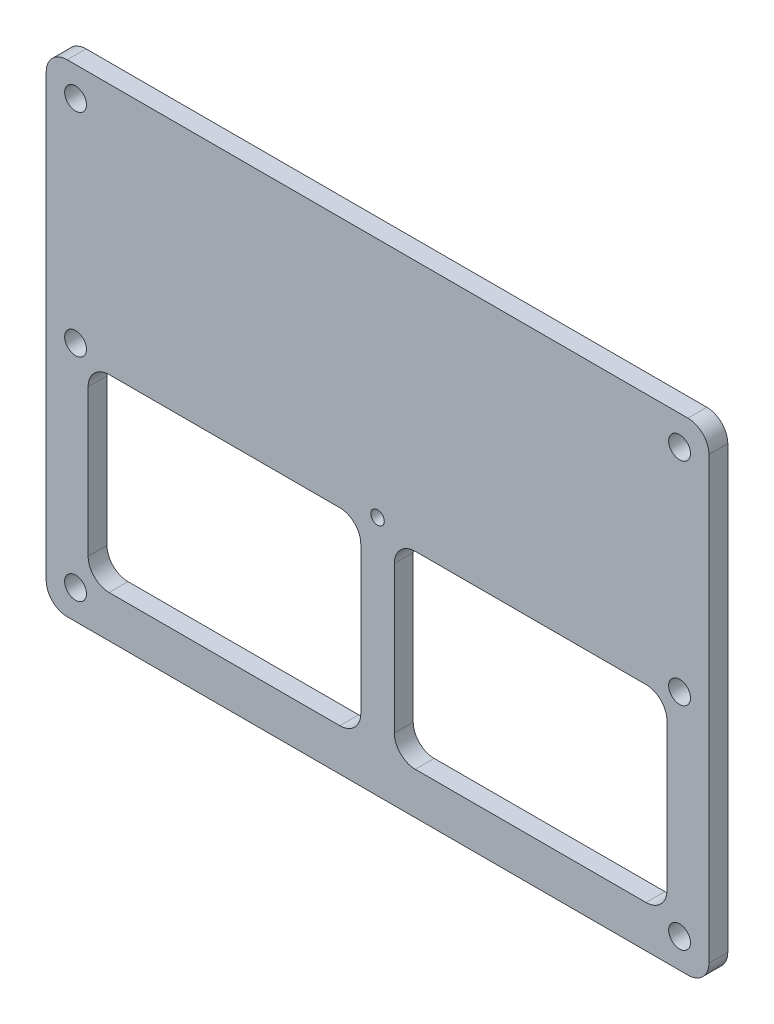
SolidWorks part; units mm, degrees
material "ABS PC"
ref_plane "前视基准面" through (0, 0, 0) normal (0, 0, 1) x (1, 0, 0)
ref_plane "上视基准面" through (0, 0, 0) normal (0, 1, 0) x (1, 0, 0)
ref_plane "右视基准面" through (0, 0, 0) normal (1, 0, 0) x (0, 0, -1)
sketch "草图1" plane through (0, 0, 0) normal (0, 0, 1) x (1, 0, 0)
  line L1 (79, -57.5) -> (-79, -57.5)
  line L2 (79, -57.5) -> (79, 57.5)
  line L3 (79, 57.5) -> (-79, 57.5)
  line L4 (-79, -57.5) -> (-79, 57.5)
  line L5 (79, -57.5) -> (-79, 57.5) construction
  line L6 (79, 57.5) -> (-79, -57.5) construction
  point P0 (0, 0)
  dimension "D1" = 158
  dimension "D2" = 115
extrude "凸台-拉伸1" add sketch "草图1" along normal blind 4.5
sketch "草图2" plane through (0, 0, 4.5) normal (0, 0, 1) x (1, 0, 0)
  line L0 (0, 57.5) -> (0, -57.5) construction
  line L1 (79, 57.5) -> (-79, 57.5) construction
  line L2 (-79, -57.5) -> (79, -57.5) construction
  line L3 (4, -7.5) -> (4, -42.5)
  line L4 (-64, -2.5) -> (-9, -2.5)
  line L5 (-69, -7.5) -> (-69, -42.5)
  line L6 (-64, -47.5) -> (-9, -47.5)
  line L7 (-4, -7.5) -> (-4, -42.5)
  line L8 (64, -47.5) -> (9, -47.5)
  line L9 (69, -7.5) -> (69, -42.5)
  line L10 (64, -2.5) -> (9, -2.5)
  line L11 (-79, 57.5) -> (-79, -57.5) construction
  line L12 (72, -50.5) -> (-72, -50.5) construction
  line L13 (72, -50.5) -> (72, 50.5) construction
  line L14 (72, 50.5) -> (-72, 50.5) construction
  line L15 (-72, -50.5) -> (-72, 50.5) construction
  line L16 (72, -50.5) -> (-72, 50.5) construction
  line L17 (72, 50.5) -> (-72, -50.5) construction
  arc A0 (-69, -42.5) -> (-64, -47.5) centre (-64, -42.5) ccw
  arc A1 (-9, -47.5) -> (-4, -42.5) centre (-9, -42.5) ccw
  arc A2 (-9, -2.5) -> (-4, -7.5) centre (-9, -7.5) cw
  arc A3 (-64, -2.5) -> (-69, -7.5) centre (-64, -7.5) ccw
  arc A4 (64, -2.5) -> (69, -7.5) centre (64, -7.5) cw
  arc A5 (9, -2.5) -> (4, -7.5) centre (9, -7.5) ccw
  arc A6 (9, -47.5) -> (4, -42.5) centre (9, -42.5) cw
  arc A7 (69, -42.5) -> (64, -47.5) centre (64, -42.5) cw
  circle A8 centre (-72, 50.5) radius 2.6
  circle A9 centre (72, 50.5) radius 2.6
  circle A10 centre (72, 0) radius 2.6
  circle A11 centre (72, -50.5) radius 2.6
  circle A12 centre (-72, -50.5) radius 2.6
  circle A13 centre (-72, 0) radius 2.6
  circle A14 centre (0, 0) radius 1.6
  point P12 (-69, -47.5)
  point P17 (-4, -2.5)
  point P20 (-69, -2.5)
  point P33 (69, -2.5)
  point P34 (4, -2.5)
  point P35 (69, -47.5)
  point P36 (0, 0)
  dimension "D4" = 5
  dimension "D6" = 5.2
  dimension "D9" = 3.2
  dimension "D1" = 65
  dimension "D2" = 45
  dimension "D3" = 8
  dimension "D5" = 10
  dimension "D7" = 7
  dimension "D8" = 7
extrude "切除-拉伸1" cut sketch "草图2" against normal blind 4.5
fillet "圆角1" radius 5 4 edges at (79, -57.5, 2.25) (-79, -57.5, 2.25) (79, 57.5, 2.25) (-79, 57.5, 2.25)
